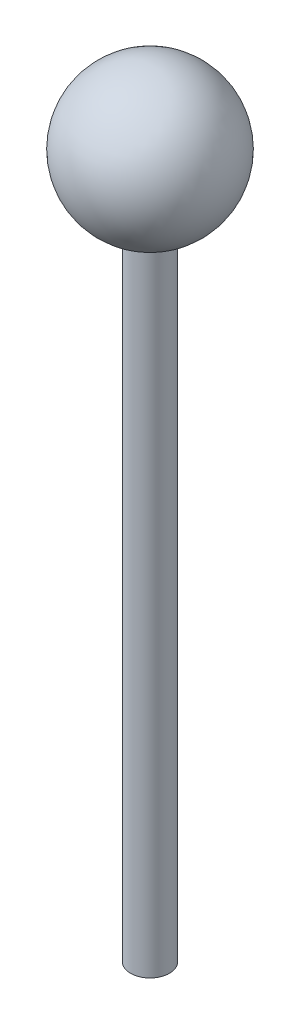
SolidWorks part; units mm, degrees
material "Alumina"
ref_plane "Front Plane" through (0, 0, 0) normal (0, 0, 1) x (1, 0, 0)
ref_plane "Top Plane" through (0, 0, 0) normal (0, 1, 0) x (1, 0, 0)
ref_plane "Right Plane" through (0, 0, 0) normal (1, 0, 0) x (0, 0, -1)
sketch "Sketch1" plane through (0, 0, 0) normal (0, 1, 0) x (1, 0, 0)
  circle A0 centre (0, 0) radius 2
  dimension "D1" = 4
extrude "Boss-Extrude1" add sketch "Sketch1" along normal blind 65
sketch "Sketch2" plane through (0, 0, 0) normal (0, 0, 1) x (1, 0, 0)
  line L0 (0, 65) -> (0, 87.6006) construction
  line L1 (2, 65) -> (-2, 65) construction
  line L2 (0, 65) -> (0, 44.2184) construction
  line L3 (0, 79.7284) -> (0, 64.7284)
  circle A0 centre (0, 72.2284) radius 7.5
  dimension "D1" = 15
revolve "Revolve2" add sketch "Sketch2" angle 360 about L0
